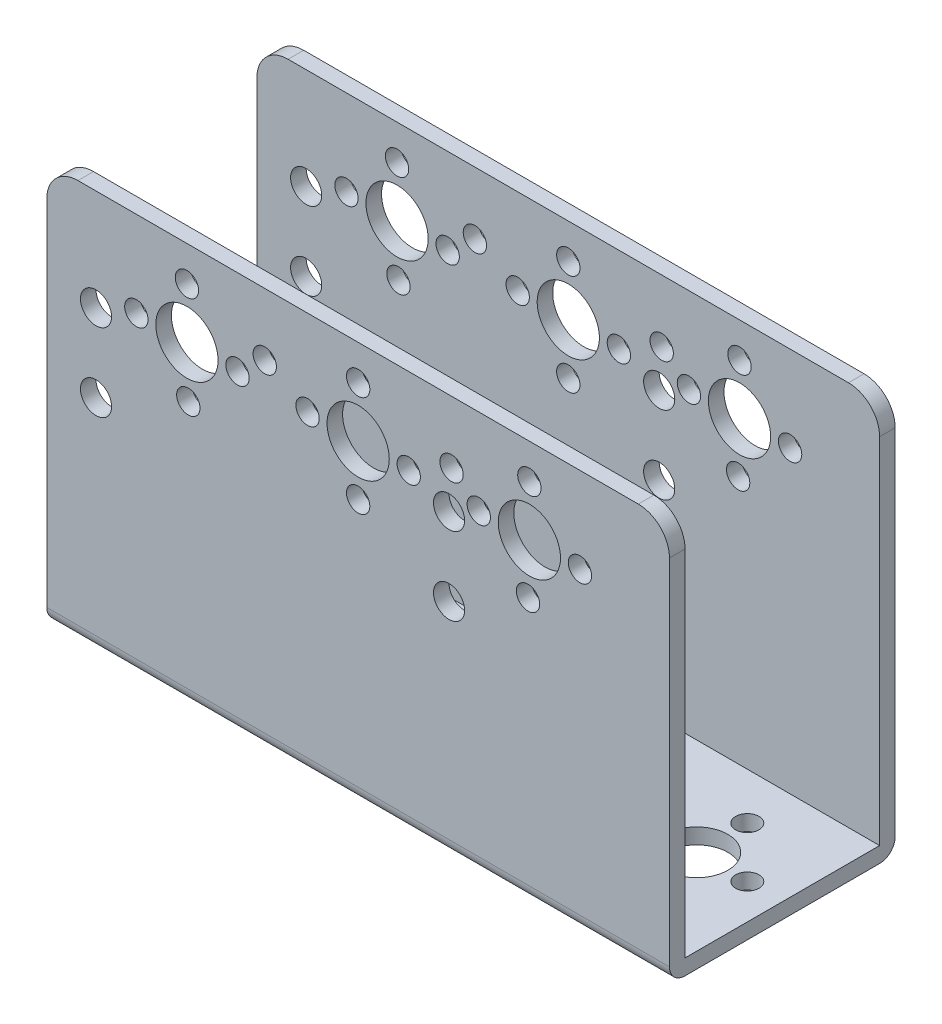
SolidWorks part; units mm, degrees
ref_plane "Front Plane" through (0, 0, 0) normal (0, 0, 1) x (1, 0, 0)
ref_plane "Top Plane" through (0, 0, 0) normal (0, 1, 0) x (1, 0, 0)
ref_plane "Right Plane" through (0, 0, 0) normal (1, 0, 0) x (0, 0, -1)
sketch "Sketch1" plane through (0, 0, 0) normal (0, 1, 0) x (1, 0, 0)
  line L1 (-40, -29) -> (40, -29)
  line L2 (-40, -29) -> (-40, 0)
  line L3 (-40, 0) -> (40, 0)
  line L4 (40, -29) -> (40, 0)
  point P4 (0, 0)
  dimension "D1" = 29
  dimension "D2" = 80
extrude "Boss-Extrude1" add sketch "Sketch1" along normal blind 51.5
sketch "Sketch2" plane through (40, 0, 0) normal (1, 0, 0) x (0, 0, -1)
  line L0 (-29, 51.5) -> (0, 51.5) construction
  line L1 (-27, 51.5) -> (-2, 51.5)
  line L2 (-27, 51.5) -> (-27, 2)
  line L3 (-27, 2) -> (-2, 2)
  line L4 (-2, 51.5) -> (-2, 2)
  line L5 (-29, 51.5) -> (-29, 0) construction
  line L6 (0, 51.5) -> (0, 0) construction
  line L7 (-29, 0) -> (0, 0) construction
  dimension "D1" = 2
  dimension "D2" = 2
  dimension "D3" = 2
extrude "Cut-Extrude1" cut sketch "Sketch2" against normal through all
fillet "Fillet6" radius 2 2 edges at (0, 0, 0) (0, 0, 29)
sketch "Sketch3" plane through (0, 2, 0) normal (0, 1, 0) x (1, 0, 0)
  line L0 (40, -27) -> (40, -2) construction
  line L1 (0, 0) -> (0, -29) construction
  line L2 (-40, -29) -> (40, -29) construction
  circle A0 centre (35.5, -14.5) radius 1.5
  circle A1 centre (29, -14.5) radius 4
  circle A2 centre (22.5, -14.5) radius 1.5
  circle A3 centre (29, -8) radius 1.5
  circle A4 centre (29, -21) radius 1.5
  circle A5 centre (-29, -21) radius 1.5
  circle A6 centre (-35.5, -14.5) radius 1.5
  circle A7 centre (-22.5, -14.5) radius 1.5
  circle A8 centre (-29, -14.5) radius 4
  circle A9 centre (-29, -8) radius 1.5
  circle A10 centre (0, -14.5) radius 4
  circle A11 centre (6.5, -14.5) radius 1.5
  circle A12 centre (-6.5, -14.5) radius 1.5
  circle A13 centre (0, -8) radius 1.5
  circle A14 centre (0, -21) radius 1.5
  dimension "D1" = 3
  dimension "D3" = 8
  dimension "D5" = 3
  dimension "D8" = 3
  dimension "D9" = 3
  dimension "D11" = 8
  dimension "D12" = 3
  dimension "D13" = 3
  dimension "D14" = 3
  dimension "D15" = 3
  dimension "D2" = 4.5
  dimension "D4" = 6.5
  dimension "D6" = 6.5
  dimension "D7" = 6.5
  dimension "D10" = 6.5
  dimension "D16" = 6.5
  dimension "D17" = 6.5
extrude "Cut-Extrude2" cut sketch "Sketch3" against normal blind 43.5
sketch "Sketch4" plane through (0, 0, 29) normal (0, 0, 1) x (1, 0, 0)
  line L0 (40, 51.5) -> (40, 2) construction
  line L1 (-40, 51.5) -> (40, 51.5) construction
  line L2 (0, 51.5) -> (0, 0) construction
  line L3 (-40, 51.5) -> (-40, 2) construction
  circle A0 centre (22, 40.5) radius 4
  circle A1 centre (15.5, 40.5) radius 1.5
  circle A2 centre (28.5, 40.5) radius 1.5
  circle A3 centre (22, 47) radius 1.5
  circle A4 centre (21.8234, 34) radius 1.5
  circle A5 centre (-21.8234, 34) radius 1.5
  circle A6 centre (-28.5, 40.5) radius 1.5
  circle A7 centre (-22, 47) radius 1.5
  circle A8 centre (-22, 40.5) radius 4
  circle A9 centre (-15.5, 40.5) radius 1.5
  circle A10 centre (0, 40.5) radius 4
  circle A11 centre (6.5, 40.5) radius 1.5
  circle A12 centre (-6.5, 40.5) radius 1.5
  circle A13 centre (0, 47) radius 1.5
  circle A14 centre (0, 34) radius 1.5
  circle A15 centre (12, 43.5) radius 1.5
  circle A16 centre (-12, 43.5) radius 1.5
  circle A17 centre (11.68, 38.5) radius 2
  circle A18 centre (11.68, 28.5) radius 2
  circle A19 centre (-33.68, 38.5) radius 2
  circle A20 centre (-33.68, 28.5) radius 2
  dimension "D8" = 3
  dimension "D9" = 3
  dimension "D10" = 3
  dimension "D11" = 3
  dimension "D14" = 8
  dimension "D16" = 3
  dimension "D17" = 3
  dimension "D18" = 3
  dimension "3" = 3
  dimension "D19" = 3
  dimension "D20" = 3
  dimension "D23" = 6.5
  dimension "D4" = 6.5
  dimension "D5" = 0
  dimension "D6" = 0
  dimension "D7" = 6.5
  dimension "D12" = 10
  dimension "D13" = 3
  dimension "D15" = 6.5
  dimension "D21" = 0
  dimension "D22" = 0
  dimension "D24" = 6.5
  dimension "D25" = 0
  dimension "D26" = 6.5
  dimension "D27" = 10
  dimension "D28" = 3
  dimension "D29" = 6.5
  dimension "D30" = 22
  dimension "D31" = 0
  dimension "D32" = 6.5
  dimension "D34" = 28.32
  dimension "D35" = 10
  dimension "D36" = 4
  dimension "D37" = 4
  dimension "D38" = 4
  dimension "D39" = 6.32
  dimension "4" = 4
  dimension "D40" = 0
  dimension "D41" = 10
  dimension "D42" = 0
  dimension "D3" = 11
  dimension "D33" = 13
extrude "Cut-Extrude3" cut sketch "Sketch4" against normal blind 43.5
fillet "Fillet7" radius 4 4 edges at (-40, 51.5, 1) (-40, 51.5, 28) (40, 51.5, 28) (40, 51.5, 1)
